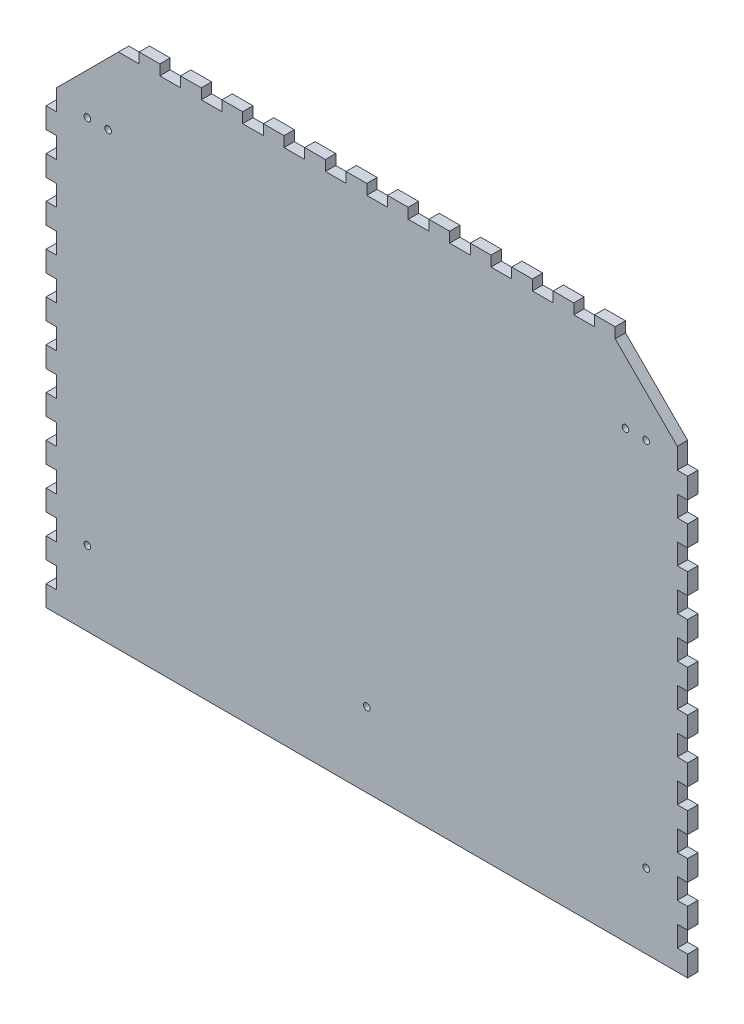
SolidWorks part; units mm, degrees
material "Buche"
ref_plane "Ebene vorne" through (0, 0, 0) normal (0, 0, 1) x (1, 0, 0)
ref_plane "Ebene oben" through (0, 0, 0) normal (0, 1, 0) x (1, 0, 0)
ref_plane "Ebene rechts" through (0, 0, 0) normal (1, 0, 0) x (0, 0, -1)
sketch "Skizze1" plane through (0, 0, 0) normal (0, 0, 1) x (1, 0, 0)
  line L0 (5, 10) -> (5, 20)
  line L1 (5, 0) -> (305, 0)
  line L2 (305, 10) -> (305, 20)
  line L3 (55, 250) -> (65, 250)
  line L4 (5, 220) -> (35, 250)
  line L5 (305, 220) -> (275, 250)
  line L6 (35, 250) -> (45, 250)
  line L7 (45, 250) -> (45, 255)
  line L8 (45, 255) -> (55, 255)
  line L9 (55, 255) -> (55, 250)
  line L10 (65, 250) -> (65, 255)
  line L11 (65, 255) -> (75, 255)
  line L12 (75, 255) -> (75, 250)
  line L13 (305, 0) -> (310, 0)
  line L14 (310, 0) -> (310, 10)
  line L15 (310, 10) -> (305, 10)
  line L16 (305, 30) -> (305, 40)
  line L17 (305, 20) -> (310, 20)
  line L18 (310, 20) -> (310, 30)
  line L19 (310, 30) -> (305, 30)
  line L20 (305, 50) -> (305, 60)
  line L21 (305, 40) -> (310, 40)
  line L22 (310, 40) -> (310, 50)
  line L23 (310, 50) -> (305, 50)
  line L24 (305, 70) -> (305, 80)
  line L25 (305, 60) -> (310, 60)
  line L26 (310, 60) -> (310, 70)
  line L27 (310, 70) -> (305, 70)
  line L28 (305, 90) -> (305, 100)
  line L29 (305, 80) -> (310, 80)
  line L30 (310, 80) -> (310, 90)
  line L31 (310, 90) -> (305, 90)
  line L32 (305, 110) -> (305, 120)
  line L33 (305, 100) -> (310, 100)
  line L34 (310, 100) -> (310, 110)
  line L35 (310, 110) -> (305, 110)
  line L36 (305, 130) -> (305, 140)
  line L37 (305, 120) -> (310, 120)
  line L38 (310, 120) -> (310, 130)
  line L39 (310, 130) -> (305, 130)
  line L40 (305, 150) -> (305, 160)
  line L41 (305, 140) -> (310, 140)
  line L42 (310, 140) -> (310, 150)
  line L43 (310, 150) -> (305, 150)
  line L44 (305, 170) -> (305, 180)
  line L45 (305, 160) -> (310, 160)
  line L46 (310, 160) -> (310, 170)
  line L47 (310, 170) -> (305, 170)
  line L48 (305, 190) -> (305, 200)
  line L49 (305, 180) -> (310, 180)
  line L50 (310, 180) -> (310, 190)
  line L51 (310, 190) -> (305, 190)
  line L52 (305, 210) -> (305, 220)
  line L53 (305, 200) -> (310, 200)
  line L54 (310, 200) -> (310, 210)
  line L55 (310, 210) -> (305, 210)
  line L56 (5, 0) -> (0, 0)
  line L57 (0, 0) -> (0, 10)
  line L58 (0, 10) -> (5, 10)
  line L59 (5, 30) -> (5, 40)
  line L60 (0, 20) -> (0, 30)
  line L61 (0, 30) -> (5, 30)
  line L62 (5, 50) -> (5, 60)
  line L63 (0, 40) -> (0, 50)
  line L64 (0, 50) -> (5, 50)
  line L65 (5, 70) -> (5, 80)
  line L66 (0, 60) -> (0, 70)
  line L67 (0, 70) -> (5, 70)
  line L68 (5, 90) -> (5, 100)
  line L69 (0, 80) -> (0, 90)
  line L70 (0, 90) -> (5, 90)
  line L71 (5, 110) -> (5, 120)
  line L72 (0, 100) -> (0, 110)
  line L73 (0, 110) -> (5, 110)
  line L74 (5, 130) -> (5, 140)
  line L75 (0, 120) -> (0, 130)
  line L76 (0, 130) -> (5, 130)
  line L77 (5, 150) -> (5, 160)
  line L78 (0, 140) -> (0, 150)
  line L79 (0, 150) -> (5, 150)
  line L80 (5, 170) -> (5, 180)
  line L81 (0, 160) -> (0, 170)
  line L82 (0, 170) -> (5, 170)
  line L83 (5, 190) -> (5, 200)
  line L84 (0, 180) -> (0, 190)
  line L85 (0, 190) -> (5, 190)
  line L86 (5, 210) -> (5, 220)
  line L87 (0, 200) -> (0, 210)
  line L88 (0, 210) -> (5, 210)
  line L89 (0, 20) -> (5, 20)
  line L90 (0, 40) -> (5, 40)
  line L91 (0, 60) -> (5, 60)
  line L92 (0, 80) -> (5, 80)
  line L93 (0, 100) -> (5, 100)
  line L94 (0, 120) -> (5, 120)
  line L95 (0, 140) -> (5, 140)
  line L96 (0, 160) -> (5, 160)
  line L97 (0, 180) -> (5, 180)
  line L98 (0, 200) -> (5, 200)
  line L99 (75, 250) -> (85, 250)
  line L100 (85, 250) -> (85, 255)
  line L101 (85, 255) -> (95, 255)
  line L102 (95, 255) -> (95, 250)
  line L103 (95, 250) -> (105, 250)
  line L104 (105, 250) -> (105, 255)
  line L105 (105, 255) -> (115, 255)
  line L106 (115, 255) -> (115, 250)
  line L107 (115, 250) -> (125, 250)
  line L108 (125, 250) -> (125, 255)
  line L109 (125, 255) -> (135, 255)
  line L110 (135, 255) -> (135, 250)
  line L111 (135, 250) -> (145, 250)
  line L112 (145, 250) -> (145, 255)
  line L113 (145, 255) -> (155, 255)
  line L114 (155, 255) -> (155, 250)
  line L115 (155, 250) -> (165, 250)
  line L116 (165, 250) -> (165, 255)
  line L117 (165, 255) -> (175, 255)
  line L118 (175, 255) -> (175, 250)
  line L119 (175, 250) -> (185, 250)
  line L120 (185, 250) -> (185, 255)
  line L121 (185, 255) -> (195, 255)
  line L122 (195, 255) -> (195, 250)
  line L123 (195, 250) -> (205, 250)
  line L124 (205, 250) -> (205, 255)
  line L125 (205, 255) -> (215, 255)
  line L126 (215, 255) -> (215, 250)
  line L127 (215, 250) -> (225, 250)
  line L128 (225, 250) -> (225, 255)
  line L129 (225, 255) -> (235, 255)
  line L130 (235, 255) -> (235, 250)
  line L131 (235, 250) -> (245, 250)
  line L132 (245, 250) -> (245, 255)
  line L133 (245, 255) -> (255, 255)
  line L134 (255, 255) -> (255, 250)
  line L135 (255, 250) -> (265, 250)
  line L136 (265, 250) -> (265, 255)
  line L137 (265, 255) -> (275, 255)
  line L138 (275, 255) -> (275, 250)
  circle A0 centre (20, 215) radius 1.6
  circle A1 centre (30, 215) radius 1.6
  circle A2 centre (290, 215) radius 1.6
  circle A3 centre (280, 215) radius 1.6
  circle A4 centre (20, 36) radius 1.6
  circle A5 centre (155, 36) radius 1.6
  circle A6 centre (290, 36) radius 1.6
  dimension "D1" = 12
extrude "Aufsatz-Linear austragen1" add sketch "Skizze1" along normal blind 5
